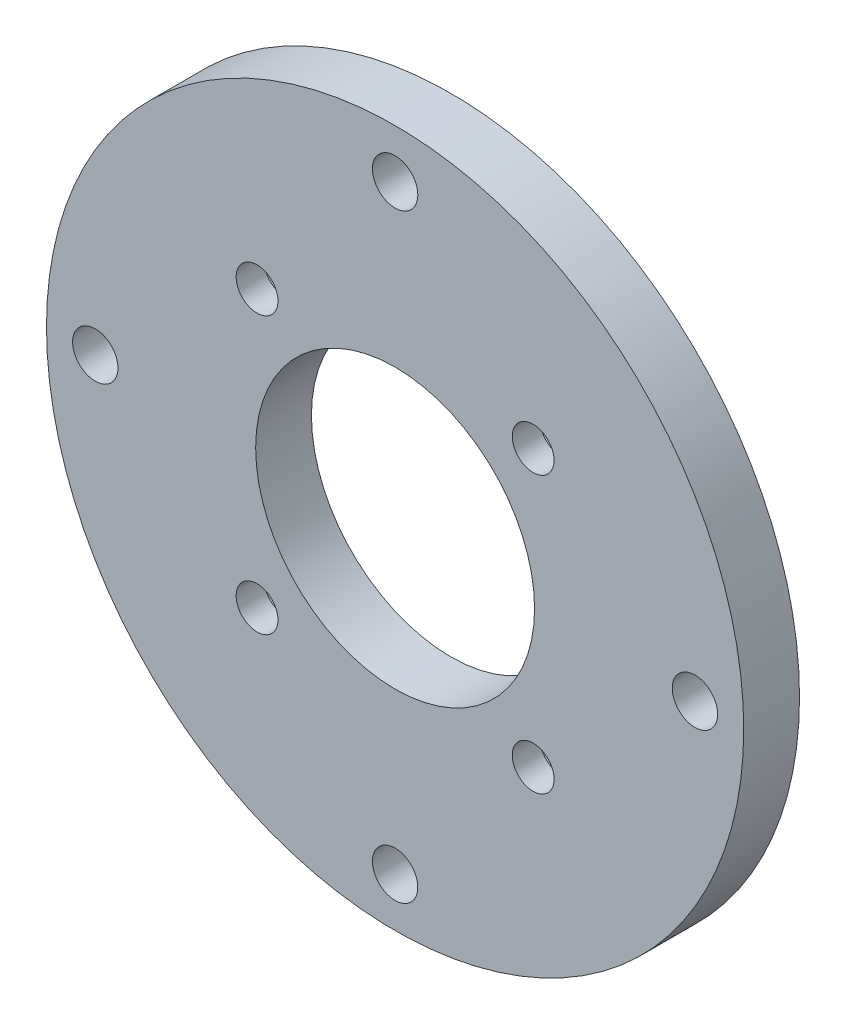
SolidWorks part; units mm, degrees
material "Plain Carbon Steel"
ref_plane "Front Plane" through (0, 0, 0) normal (0, 0, 1) x (1, 0, 0)
ref_plane "Top Plane" through (0, 0, 0) normal (0, 1, 0) x (1, 0, 0)
ref_plane "Right Plane" through (0, 0, 0) normal (1, 0, 0) x (0, 0, -1)
sketch "Sketch1" plane through (0, 0, 0) normal (0, 0, 1) x (1, 0, 0)
  circle A0 centre (0, 0) radius 125
  dimension "D1" = 250
extrude "Boss-Extrude1" add sketch "Sketch1" along normal blind 20
sketch "Sketch2" plane through (0, 0, 20) normal (0, 0, 1) x (1, 0, 0)
  circle A0 centre (0, 0) radius 50
  dimension "D1" = 100
extrude "Cut-Extrude1" cut sketch "Sketch2" against normal blind 20
sketch "Sketch3" plane through (0, 0, 20) normal (0, 0, 1) x (1, 0, 0)
  circle A0 centre (0, 107.5) radius 8.1328
  dimension "D2" = 16.2656
  dimension "D1" = 107.5
extrude "Cut-Extrude2" cut sketch "Sketch3" against normal blind 20
sketch "Sketch4" plane through (0, 0, 0) normal (0, 0, -1) x (-1, 0, 0)
  line L1 (-49.4975, -49.4975) -> (49.4975, -49.4975) construction
  line L2 (-49.4975, -49.4975) -> (-49.4975, 49.4975) construction
  line L3 (-49.4975, 49.4975) -> (49.4975, 49.4975) construction
  line L4 (49.4975, -49.4975) -> (49.4975, 49.4975) construction
  line L5 (-49.4975, -49.4975) -> (49.4975, 49.4975) construction
  line L6 (-49.4975, 49.4975) -> (49.4975, -49.4975) construction
  circle A0 centre (49.4975, 49.4975) radius 15
  point P0 (0, 0)
  dimension "D2" = 30
  dimension "D1" = 70
extrude "Cut-Extrude3" cut sketch "Sketch4" against normal blind 10
sketch "Sketch5" plane through (0, 0, 10) normal (0, 0, -1) x (-1, 0, 0)
  circle A0 centre (49.4975, 49.4975) radius 7.5
  dimension "D1" = 15
extrude "Cut-Extrude4" cut sketch "Sketch5" against normal blind 10
pattern_circular "CirPattern1" count 4 over 360 about axis through (0, 0, 0) along (0, 0, 1) of "Cut-Extrude2", "Cut-Extrude3", "Cut-Extrude4"
